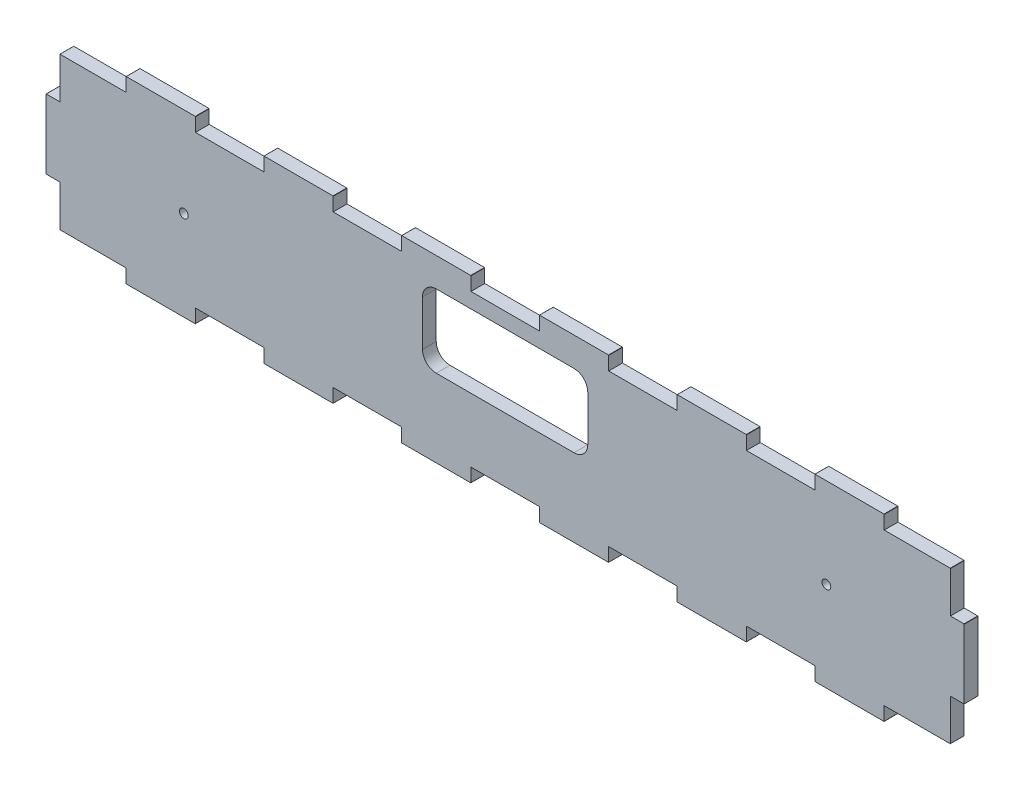
SolidWorks part; units mm, degrees
ref_plane "Front Plane" through (0, 0, 0) normal (0, 0, 1) x (1, 0, 0)
ref_plane "Top Plane" through (0, 0, 0) normal (0, 1, 0) x (1, 0, 0)
ref_plane "Right Plane" through (0, 0, 0) normal (1, 0, 0) x (0, 0, -1)
sketch "Model" plane through (0, 0, 0) normal (0, 0, 1) x (1, 0, 0)
  line L0 (-112.44, -32.58) -> (-112.43, -32.57)
  line L1 (-112.43, -32.57) -> (-112.42, -32.55)
  line L2 (-112.42, -32.55) -> (-112.41, -32.54)
  line L3 (-112.41, -32.54) -> (-112.4, -32.52)
  line L4 (-112.4, -32.52) -> (-112.4, -27.6)
  line L5 (-112.4, -27.6) -> (-87.6, -27.6)
  line L6 (-87.6, -27.6) -> (-87.6, -32.52)
  line L7 (-87.6, -32.52) -> (-87.58, -32.56)
  line L8 (-87.58, -32.56) -> (-87.57, -32.57)
  line L9 (-87.57, -32.57) -> (-87.55, -32.58)
  line L10 (-87.55, -32.58) -> (-87.54, -32.59)
  line L11 (-87.54, -32.59) -> (-87.52, -32.6)
  line L12 (-87.52, -32.6) -> (-62.48, -32.6)
  line L13 (-62.48, -32.6) -> (-62.44, -32.58)
  line L14 (-62.44, -32.58) -> (-62.43, -32.57)
  line L15 (-62.43, -32.57) -> (-62.42, -32.55)
  line L16 (-62.42, -32.55) -> (-62.41, -32.54)
  line L17 (-62.41, -32.54) -> (-62.4, -32.52)
  line L18 (-62.4, -32.52) -> (-62.4, -27.6)
  line L19 (-62.4, -27.6) -> (-37.6, -27.6)
  line L20 (-37.6, -27.6) -> (-37.6, -32.52)
  line L21 (-37.6, -32.52) -> (-37.58, -32.56)
  line L22 (-37.58, -32.56) -> (-37.57, -32.57)
  line L23 (-37.57, -32.57) -> (-37.55, -32.58)
  line L24 (-37.55, -32.58) -> (-37.54, -32.59)
  line L25 (-37.54, -32.59) -> (-37.52, -32.6)
  line L26 (-37.52, -32.6) -> (-12.48, -32.6)
  line L27 (-12.48, -32.6) -> (-12.44, -32.58)
  line L28 (-12.44, -32.58) -> (-12.43, -32.57)
  line L29 (-12.43, -32.57) -> (-12.42, -32.55)
  line L30 (-12.42, -32.55) -> (-12.41, -32.54)
  line L31 (-12.41, -32.54) -> (-12.4, -32.52)
  line L32 (-12.4, -32.52) -> (-12.4, -27.6)
  line L33 (-12.4, -27.6) -> (12.4, -27.6)
  line L34 (12.4, -27.6) -> (12.4, -32.52)
  line L35 (12.4, -32.52) -> (12.42, -32.56)
  line L36 (12.42, -32.56) -> (12.43, -32.57)
  line L37 (12.43, -32.57) -> (12.45, -32.58)
  line L38 (12.45, -32.58) -> (12.46, -32.59)
  line L39 (12.46, -32.59) -> (12.48, -32.6)
  line L40 (12.48, -32.6) -> (37.52, -32.6)
  line L41 (37.52, -32.6) -> (37.56, -32.58)
  line L42 (37.56, -32.58) -> (37.57, -32.57)
  line L43 (37.57, -32.57) -> (37.58, -32.55)
  line L44 (37.58, -32.55) -> (37.59, -32.54)
  line L45 (37.59, -32.54) -> (37.6, -32.52)
  line L46 (37.6, -32.52) -> (37.6, -27.6)
  line L47 (37.6, -27.6) -> (62.4, -27.6)
  line L48 (62.4, -27.6) -> (62.4, -32.52)
  line L49 (62.4, -32.52) -> (62.42, -32.56)
  line L50 (62.42, -32.56) -> (62.43, -32.57)
  line L51 (62.43, -32.57) -> (62.45, -32.58)
  line L52 (62.45, -32.58) -> (62.46, -32.59)
  line L53 (62.46, -32.59) -> (62.48, -32.6)
  line L54 (62.48, -32.6) -> (87.52, -32.6)
  line L55 (87.52, -32.6) -> (87.56, -32.58)
  line L56 (87.56, -32.58) -> (87.57, -32.57)
  line L57 (87.57, -32.57) -> (87.58, -32.55)
  line L58 (87.58, -32.55) -> (87.59, -32.54)
  line L59 (87.59, -32.54) -> (87.6, -32.52)
  line L60 (87.6, -32.52) -> (87.6, -27.6)
  line L61 (87.6, -27.6) -> (112.4, -27.6)
  line L62 (112.4, -27.6) -> (112.4, -32.52)
  line L63 (112.4, -32.52) -> (112.42, -32.56)
  line L64 (112.42, -32.56) -> (112.43, -32.57)
  line L65 (112.43, -32.57) -> (112.45, -32.58)
  line L66 (112.45, -32.58) -> (112.46, -32.59)
  line L67 (112.46, -32.59) -> (112.48, -32.6)
  line L68 (112.48, -32.6) -> (137.52, -32.6)
  line L69 (137.52, -32.6) -> (137.56, -32.58)
  line L70 (137.56, -32.58) -> (137.57, -32.57)
  line L71 (137.57, -32.57) -> (137.58, -32.55)
  line L72 (137.58, -32.55) -> (137.59, -32.54)
  line L73 (137.59, -32.54) -> (137.6, -32.52)
  line L74 (137.6, -32.52) -> (137.6, -27.6)
  line L75 (137.6, -27.6) -> (161.56, -27.6)
  line L76 (161.56, -27.6) -> (161.6, -27.58)
  line L77 (161.6, -27.58) -> (161.61, -27.57)
  line L78 (161.61, -27.57) -> (161.62, -27.55)
  line L79 (161.62, -27.55) -> (161.63, -27.54)
  line L80 (161.63, -27.54) -> (161.64, -27.52)
  line L81 (161.64, -27.52) -> (161.64, -12.6)
  line L82 (161.64, -12.6) -> (166.56, -12.6)
  line L83 (166.56, -12.6) -> (166.6, -12.58)
  line L84 (166.6, -12.58) -> (166.61, -12.57)
  line L85 (166.61, -12.57) -> (166.62, -12.55)
  line L86 (166.62, -12.55) -> (166.63, -12.54)
  line L87 (166.63, -12.54) -> (166.64, -12.52)
  line L88 (166.64, -12.52) -> (166.64, 12.52)
  line L89 (166.64, 12.52) -> (166.62, 12.56)
  line L90 (166.62, 12.56) -> (166.61, 12.57)
  line L91 (166.61, 12.57) -> (166.59, 12.58)
  line L92 (166.59, 12.58) -> (166.58, 12.59)
  line L93 (166.58, 12.59) -> (166.56, 12.6)
  line L94 (166.56, 12.6) -> (161.64, 12.6)
  line L95 (161.64, 12.6) -> (161.64, 27.52)
  line L96 (161.64, 27.52) -> (161.62, 27.56)
  line L97 (161.62, 27.56) -> (161.61, 27.57)
  line L98 (161.61, 27.57) -> (161.59, 27.58)
  line L99 (161.59, 27.58) -> (161.58, 27.59)
  line L100 (161.58, 27.59) -> (161.56, 27.6)
  line L101 (161.56, 27.6) -> (137.6, 27.6)
  line L102 (137.6, 27.6) -> (137.6, 32.52)
  line L103 (137.6, 32.52) -> (137.58, 32.56)
  line L104 (137.58, 32.56) -> (137.57, 32.57)
  line L105 (137.57, 32.57) -> (137.55, 32.58)
  line L106 (137.55, 32.58) -> (137.54, 32.59)
  line L107 (137.54, 32.59) -> (137.52, 32.6)
  line L108 (137.52, 32.6) -> (112.48, 32.6)
  line L109 (112.48, 32.6) -> (112.44, 32.58)
  line L110 (112.44, 32.58) -> (112.43, 32.57)
  line L111 (112.43, 32.57) -> (112.42, 32.55)
  line L112 (112.42, 32.55) -> (112.41, 32.54)
  line L113 (112.41, 32.54) -> (112.4, 32.52)
  line L114 (112.4, 32.52) -> (112.4, 27.6)
  line L115 (112.4, 27.6) -> (87.6, 27.6)
  line L116 (87.6, 27.6) -> (87.6, 32.52)
  line L117 (87.6, 32.52) -> (87.58, 32.56)
  line L118 (87.58, 32.56) -> (87.57, 32.57)
  line L119 (87.57, 32.57) -> (87.55, 32.58)
  line L120 (87.55, 32.58) -> (87.54, 32.59)
  line L121 (87.54, 32.59) -> (87.52, 32.6)
  line L122 (87.52, 32.6) -> (62.48, 32.6)
  line L123 (62.48, 32.6) -> (62.44, 32.58)
  line L124 (62.44, 32.58) -> (62.43, 32.57)
  line L125 (62.43, 32.57) -> (62.42, 32.55)
  line L126 (62.42, 32.55) -> (62.41, 32.54)
  line L127 (62.41, 32.54) -> (62.4, 32.52)
  line L128 (62.4, 32.52) -> (62.4, 27.6)
  line L129 (62.4, 27.6) -> (37.6, 27.6)
  line L130 (37.6, 27.6) -> (37.6, 32.52)
  line L131 (37.6, 32.52) -> (37.58, 32.56)
  line L132 (37.58, 32.56) -> (37.57, 32.57)
  line L133 (37.57, 32.57) -> (37.55, 32.58)
  line L134 (37.55, 32.58) -> (37.54, 32.59)
  line L135 (37.54, 32.59) -> (37.52, 32.6)
  line L136 (37.52, 32.6) -> (12.48, 32.6)
  line L137 (12.48, 32.6) -> (12.44, 32.58)
  line L138 (12.44, 32.58) -> (12.43, 32.57)
  line L139 (12.43, 32.57) -> (12.42, 32.55)
  line L140 (12.42, 32.55) -> (12.41, 32.54)
  line L141 (12.41, 32.54) -> (12.4, 32.52)
  line L142 (12.4, 32.52) -> (12.4, 27.6)
  line L143 (12.4, 27.6) -> (-12.4, 27.6)
  line L144 (-12.4, 27.6) -> (-12.4, 32.52)
  line L145 (-12.4, 32.52) -> (-12.42, 32.56)
  line L146 (-12.42, 32.56) -> (-12.43, 32.57)
  line L147 (-12.43, 32.57) -> (-12.45, 32.58)
  line L148 (-12.45, 32.58) -> (-12.46, 32.59)
  line L149 (-12.46, 32.59) -> (-12.48, 32.6)
  line L150 (-12.48, 32.6) -> (-37.52, 32.6)
  line L151 (-37.52, 32.6) -> (-37.56, 32.58)
  line L152 (-37.56, 32.58) -> (-37.57, 32.57)
  line L153 (-37.57, 32.57) -> (-37.58, 32.55)
  line L154 (-37.58, 32.55) -> (-37.59, 32.54)
  line L155 (-37.59, 32.54) -> (-37.6, 32.52)
  line L156 (-37.6, 32.52) -> (-37.6, 27.6)
  line L157 (-37.6, 27.6) -> (-62.4, 27.6)
  line L158 (-62.4, 27.6) -> (-62.4, 32.52)
  line L159 (-62.4, 32.52) -> (-62.42, 32.56)
  line L160 (-62.42, 32.56) -> (-62.43, 32.57)
  line L161 (-62.43, 32.57) -> (-62.45, 32.58)
  line L162 (-62.45, 32.58) -> (-62.46, 32.59)
  line L163 (-62.46, 32.59) -> (-62.48, 32.6)
  line L164 (-62.48, 32.6) -> (-87.52, 32.6)
  line L165 (-87.52, 32.6) -> (-87.56, 32.58)
  line L166 (-87.56, 32.58) -> (-87.57, 32.57)
  line L167 (-87.57, 32.57) -> (-87.58, 32.55)
  line L168 (-87.58, 32.55) -> (-87.59, 32.54)
  line L169 (-87.59, 32.54) -> (-87.6, 32.52)
  line L170 (-87.6, 32.52) -> (-87.6, 27.6)
  line L171 (-87.6, 27.6) -> (-112.4, 27.6)
  line L172 (-112.4, 27.6) -> (-112.4, 32.52)
  line L173 (-112.4, 32.52) -> (-112.42, 32.56)
  line L174 (-112.42, 32.56) -> (-112.43, 32.57)
  line L175 (-112.43, 32.57) -> (-112.45, 32.58)
  line L176 (-112.45, 32.58) -> (-112.46, 32.59)
  line L177 (-112.46, 32.59) -> (-112.48, 32.6)
  line L178 (-112.48, 32.6) -> (-137.52, 32.6)
  line L179 (-137.52, 32.6) -> (-137.56, 32.58)
  line L180 (-137.56, 32.58) -> (-137.57, 32.57)
  line L181 (-137.57, 32.57) -> (-137.58, 32.55)
  line L182 (-137.58, 32.55) -> (-137.59, 32.54)
  line L183 (-137.59, 32.54) -> (-137.6, 32.52)
  line L184 (-137.6, 32.52) -> (-137.6, 27.6)
  line L185 (-137.6, 27.6) -> (-161.56, 27.6)
  line L186 (-161.56, 27.6) -> (-161.6, 27.58)
  line L187 (-161.6, 27.58) -> (-161.61, 27.57)
  line L188 (-161.61, 27.57) -> (-161.62, 27.55)
  line L189 (-161.62, 27.55) -> (-161.63, 27.54)
  line L190 (-161.63, 27.54) -> (-161.64, 27.52)
  line L191 (-161.64, 27.52) -> (-161.64, 12.6)
  line L192 (-161.64, 12.6) -> (-166.56, 12.6)
  line L193 (-166.56, 12.6) -> (-166.6, 12.58)
  line L194 (-166.6, 12.58) -> (-166.61, 12.57)
  line L195 (-166.61, 12.57) -> (-166.62, 12.55)
  line L196 (-166.62, 12.55) -> (-166.63, 12.54)
  line L197 (-166.63, 12.54) -> (-166.64, 12.52)
  line L198 (-166.64, 12.52) -> (-166.64, -12.52)
  line L199 (-166.64, -12.52) -> (-166.62, -12.56)
  line L200 (-166.62, -12.56) -> (-166.61, -12.57)
  line L201 (-166.61, -12.57) -> (-166.59, -12.58)
  line L202 (-166.59, -12.58) -> (-166.58, -12.59)
  line L203 (-166.58, -12.59) -> (-166.56, -12.6)
  line L204 (-166.56, -12.6) -> (-161.64, -12.6)
  line L205 (-161.64, -12.6) -> (-161.64, -27.52)
  line L206 (-161.64, -27.52) -> (-161.62, -27.56)
  line L207 (-161.62, -27.56) -> (-161.61, -27.57)
  line L208 (-161.61, -27.57) -> (-161.59, -27.58)
  line L209 (-161.59, -27.58) -> (-161.58, -27.59)
  line L210 (-161.58, -27.59) -> (-161.56, -27.6)
  line L211 (-161.56, -27.6) -> (-137.6, -27.6)
  line L212 (-137.6, -27.6) -> (-137.6, -32.52)
  line L213 (-137.6, -32.52) -> (-137.58, -32.56)
  line L214 (-137.58, -32.56) -> (-137.57, -32.57)
  line L215 (-137.57, -32.57) -> (-137.55, -32.58)
  line L216 (-137.55, -32.58) -> (-137.54, -32.59)
  line L217 (-137.54, -32.59) -> (-137.52, -32.6)
  line L218 (-137.52, -32.6) -> (-112.48, -32.6)
  line L219 (-112.48, -32.6) -> (-112.44, -32.58)
extrude "Boss-Extrude1" add sketch "Model" along normal blind 5
sketch "Sketch1" plane through (0, 0, 5) normal (0, 0, 1) x (1, 0, 0)
  line L0 (0, 0) -> (0, -27.52) construction
  line L1 (-161.64, 27.52) -> (161.64, 27.52) construction
  line L2 (-161.64, 27.52) -> (-161.64, -27.52) construction
  line L3 (-161.64, -27.52) -> (161.64, -27.52) construction
  line L4 (161.64, 27.52) -> (161.64, -27.52) construction
  line L5 (-161.64, 27.52) -> (161.64, -27.52) construction
  line L6 (-161.64, -27.52) -> (161.64, 27.52) construction
  circle A0 centre (-116.605, 0) radius 1.6
  circle A1 centre (116.605, 0) radius 1.6
  point P4 (0, 0)
  dimension "D1" = 3.2
  dimension "D2" = 233.21
extrude "Cut-Extrude1" cut sketch "Sketch1" against normal through all
sketch "Sketch2" plane through (0, 0, 5) normal (0, 0, 1) x (1, 0, 0)
  line L0 (12.4, 27.6) -> (-12.4, 27.6) construction
  line L1 (-25, 22.1) -> (25, 22.1)
  line L2 (-30, 17.1) -> (-30, 0.6)
  line L3 (-25, -4.4) -> (25, -4.4)
  line L4 (30, 17.1) -> (30, 0.6)
  line L5 (-30, 22.1) -> (30, -4.4) construction
  line L6 (-30, -4.4) -> (30, 22.1) construction
  arc A0 (25, 22.1) -> (30, 17.1) centre (25, 17.1) cw
  arc A1 (25, -4.4) -> (30, 0.6) centre (25, 0.6) ccw
  arc A2 (-30, 0.6) -> (-25, -4.4) centre (-25, 0.6) ccw
  arc A3 (-25, 22.1) -> (-30, 17.1) centre (-25, 17.1) ccw
  point P4 (0, 8.85)
  dimension "D4" = 5
  dimension "D1" = 26.5
  dimension "D2" = 60
  dimension "D3" = 5.5
extrude "Cut-Extrude2" cut sketch "Sketch2" against normal through all
